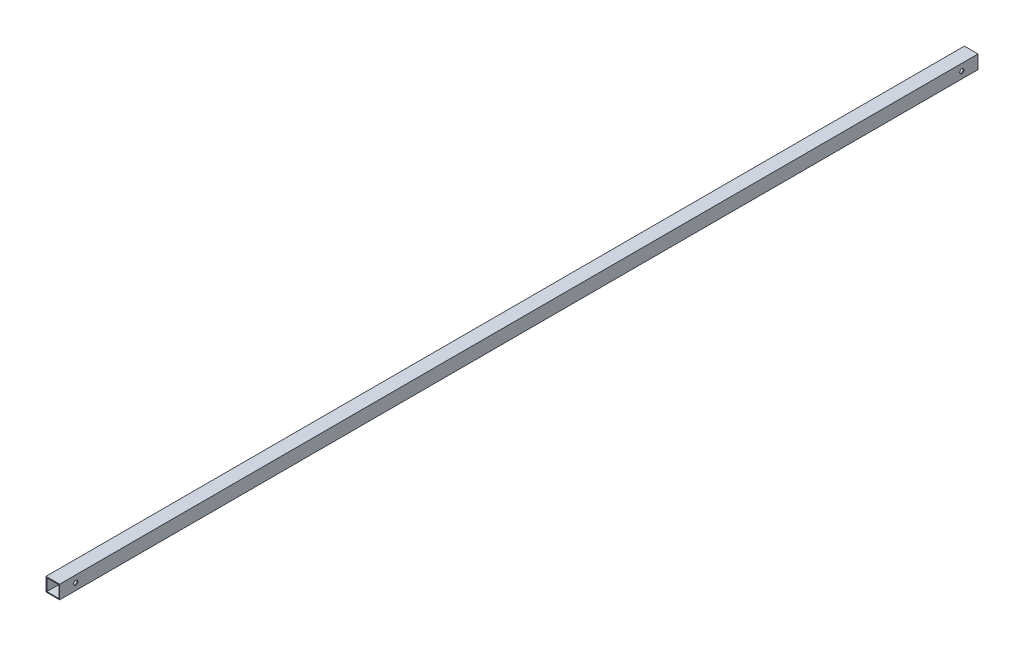
SolidWorks part; units mm, degrees
material "Aleación 1060"
ref_plane "Alzado" through (0, 0, 0) normal (0, 0, 1) x (1, 0, 0)
ref_plane "Planta" through (0, 0, 0) normal (0, 1, 0) x (1, 0, 0)
ref_plane "Vista lateral" through (0, 0, 0) normal (1, 0, 0) x (0, 0, -1)
sketch "Croquis1" plane through (0, 0, 0) normal (0, 0, 1) x (1, 0, 0)
  line L1 (8, -8) -> (-8, -8)
  line L2 (8, -8) -> (8, 8)
  line L3 (8, 8) -> (-8, 8)
  line L4 (-8, -8) -> (-8, 8)
  line L5 (8, -8) -> (-8, 8) construction
  line L6 (8, 8) -> (-8, -8) construction
  point P0 (0, 0)
  dimension "D1" = 16
  dimension "D2" = 16
extrude "Extruir-Lámina1" add sketch "Croquis1" along normal mid plane 1080 thin
sketch "Croquis2" plane through (8, 0, 0) normal (1, 0, 0) x (0, 0, -1)
  line L0 (0, 0) -> (-521, 0) construction
  line L1 (0, 0) -> (0, 8) construction
  line L2 (-540, 8) -> (540, 8) construction
  circle A0 centre (-521, 0) radius 2.5
  circle A1 centre (521, 0) radius 2.5
  dimension "D1" = 5
  dimension "D2" = 521
extrude "Extruir1" cut sketch "Croquis2" against normal through all
